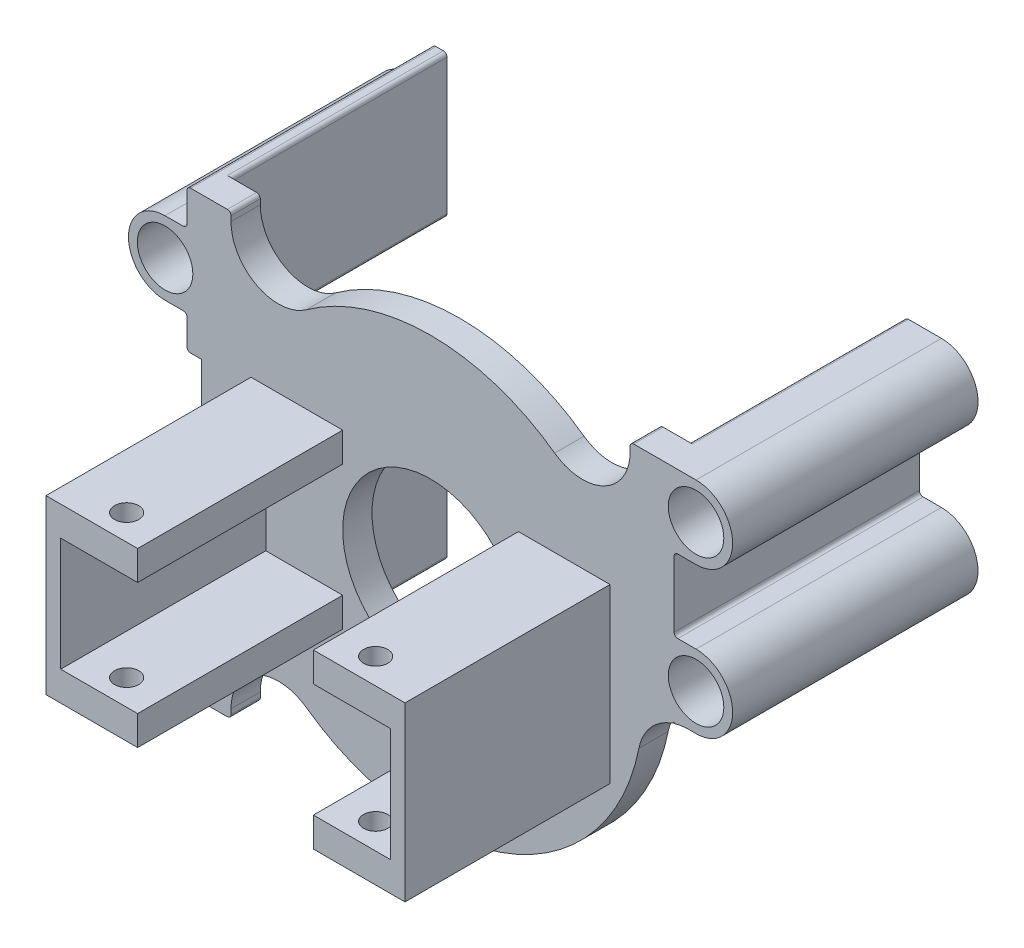
SolidWorks part; units mm, degrees
ref_plane "Front Plane" through (0, 0, 0) normal (0, 0, 1) x (1, 0, 0)
ref_plane "Top Plane" through (0, 0, 0) normal (0, 1, 0) x (1, 0, 0)
ref_plane "Right Plane" through (0, 0, 0) normal (1, 0, 0) x (0, 0, -1)
sketch "Sketch1" plane through (0, 0, 0) normal (0, 0, 1) x (1, 0, 0)
  line L15 (-5, 56.25) -> (-2.51, 56.25)
  line L22 (67.5, 41.2517) -> (65.01, 41.2517)
  line L27 (64.51, 50.75) -> (64.51, 41.7517)
  line L28 (66.555, 31.2587) -> (67.5, 31.2517)
  line L30 (-2.01, 60.75) -> (-2.01, 56.75)
  line L33 (-5, 46.25) -> (-2.51, 46.25)
  line L35 (-5, 16.25) -> (-2.51, 16.25)
  line L36 (-2.01, 5.75) -> (-2.01, 1.75)
  line L37 (-5, 6.25) -> (-2.51, 6.25)
  line L39 (-1.51, 1.25) -> (3.5, 1.25)
  line L40 (67.5, 51.25) -> (65.01, 51.25)
  line L43 (58.5, 60.75) -> (58.5, 60.0543)
  line L44 (67.5, 61.25) -> (59, 61.25)
  line L45 (3.5, 61.25) -> (-1.51, 61.25)
  line L46 (4, 2.4457) -> (4, 1.75)
  line L47 (4, 60.75) -> (4, 60.0543)
  line L48 (-2.01, 45.75) -> (-2.01, 42.25)
  line L49 (-2.01, 20.25) -> (-2.01, 16.75)
  line L52 (-1.51, 41.75) -> (0, 41.75)
  line L54 (-1.51, 20.75) -> (0, 20.75)
  line L55 (0, 41.75) -> (0, 20.75)
  circle A3 centre (-5, 51.25) radius 1.79
  circle A4 centre (-5, 11.25) radius 1.79
  arc A7 (-5, 56.25) -> (-5, 46.25) centre (-5, 51.25) ccw
  arc A8 (-5, 16.25) -> (-5, 6.25) centre (-5, 11.25) ccw
  arc A9 (67.5, 51.25) -> (67.5, 61.25) centre (67.5, 56.25) ccw
  arc A15 (66.555, 31.2587) -> (59.6979, 25.6181) centre (66.5646, 24.2587) ccw
  arc A23 (65.01, 51.25) -> (64.51, 50.75) centre (65.01, 50.75) ccw
  arc A27 (-2.51, 6.25) -> (-2.01, 5.75) centre (-2.51, 5.75) cw
  arc A28 (-2.51, 16.25) -> (-2.01, 16.75) centre (-2.51, 16.75) ccw
  arc A29 (-2.51, 46.25) -> (-2.01, 45.75) centre (-2.51, 45.75) cw
  arc A30 (-2.51, 56.25) -> (-2.01, 56.75) centre (-2.51, 56.75) ccw
  arc A34 (67.5, 31.2517) -> (67.5, 41.2517) centre (67.5, 36.2517) ccw
  arc A35 (65.01, 41.2517) -> (64.51, 41.7517) centre (65.01, 41.7517) cw
  circle A36 centre (67.5, 36.2517) radius 1.79
  circle A37 centre (31.25, 31.25) radius 12
  arc A41 (48.2007, 54.7803) -> (14.2993, 54.7803) centre (31.25, 31.25) ccw
  arc A42 (14.2993, 7.7197) -> (59.6979, 25.6181) centre (31.25, 31.25) ccw
  arc A43 (59, 61.25) -> (58.5, 60.75) centre (59, 60.75) ccw
  arc A44 (3.5, 1.25) -> (4, 1.75) centre (3.5, 1.75) ccw
  arc A45 (-2.01, 1.75) -> (-1.51, 1.25) centre (-1.51, 1.75) ccw
  arc A46 (3.5, 61.25) -> (4, 60.75) centre (3.5, 60.75) cw
  arc A47 (-1.51, 61.25) -> (-2.01, 60.75) centre (-1.51, 60.75) ccw
  arc A48 (14.2993, 7.7197) -> (4, 2.4457) centre (10.5, 2.4457) ccw
  arc A49 (48.2007, 54.7803) -> (58.5, 60.0543) centre (52, 60.0543) ccw
  arc A50 (14.2993, 54.7803) -> (4, 60.0543) centre (10.5, 60.0543) cw
  arc A51 (-2.01, 42.25) -> (-1.51, 41.75) centre (-1.51, 42.25) ccw
  arc A52 (-2.01, 20.25) -> (-1.51, 20.75) centre (-1.51, 20.25) cw
  circle A53 centre (67.5, 56.25) radius 1.79
extrude "Boss-Extrude1" add sketch "Sketch1" along normal blind 61.5
sketch "Sketch2" plane through (0, 0, 0) normal (0, 0, 1) x (1, 0, 0)
  line L2 (0, 1.75) -> (0, 20.25)
  line L4 (62.5, 1.25) -> (62.5, 29.9577)
  line L5 (66.555, 31.2587) -> (63, 31.2587)
  line L7 (62.5, 31.7587) -> (62.5, 60.75)
  line L9 (62.5, 61.25) -> (0, 61.25)
  line L14 (0, 1.25) -> (62.5, 1.25)
  line L17 (0, 61.25) -> (-0.5, 61.25)
  line L54 (0, 41.75) -> (-0.5, 41.75)
  line L55 (63, 61.25) -> (62.5, 61.25)
  line L56 (0, 42.25) -> (0, 60.75)
  line L57 (0, 20.75) -> (-0.5, 20.75)
  line L58 (0, 20.75) -> (0, 41.75)
  line L61 (0, 1.25) -> (-0.5, 1.25)
  arc A0 (0, 60.75) -> (-0.5, 61.25) centre (-0.5, 60.75) ccw
  arc A10 (63, 31.2587) -> (62.5, 31.7587) centre (63, 31.7587) cw
  arc A11 (66.555, 31.2587) -> (62.5, 29.9577) centre (66.5646, 24.2587) ccw
  arc A13 (63, 61.25) -> (62.5, 60.75) centre (63, 60.75) ccw
  arc A14 (-0.5, 1.25) -> (0, 1.75) centre (-0.5, 1.75) ccw
  arc A16 (0, 20.25) -> (-0.5, 20.75) centre (-0.5, 20.25) ccw
  arc A17 (-0.5, 41.75) -> (0, 42.25) centre (-0.5, 42.25) ccw
extrude "Cut-Extrude1" cut sketch "Sketch2" along normal blind 29.5
sketch "Sketch3" plane through (0, 0, 61.5) normal (0, 0, 1) x (1, 0, 0)
  line L14 (64.51, 31.3102) -> (64.51, 30.9504)
  arc A2 (64.51, 31.3102) -> (64.1803, 30.8401) centre (64.01, 31.3102) cw
  arc A9 (64.51, 30.9504) -> (64.1803, 30.8401) centre (66.5646, 24.2587) ccw
  circle A10 centre (67.5, 36.2517) radius 3.79
  circle A11 centre (-5, 11.25) radius 3.79
  circle A12 centre (-5, 51.25) radius 3.79
  circle A13 centre (67.5, 56.25) radius 3.79
extrude "Cut-Extrude2" cut sketch "Sketch3" against normal offset from surface (54.5 mm away) 7 up to face at (69.29, 56.25, 0)
sketch "Sketch4" plane through (0, 0, 61.5) normal (0, 0, 1) x (1, 0, 0)
  line L1 (19.25, 43.02) -> (6.74, 43.02)
  line L2 (8.75, 23.5) -> (19.25, 23.5)
  line L4 (8.75, 39) -> (19.25, 39)
  line L5 (19.25, 19.48) -> (6.74, 19.48)
  line L6 (43.25, 19.48) -> (55.76, 19.48)
  line L11 (43.25, 19.48) -> (43.25, 23.5)
  line L13 (43.25, 39) -> (43.25, 43.02)
  line L14 (8.75, 23.5) -> (8.75, 39)
  line L15 (19.25, 39) -> (19.25, 43.02)
  line L16 (19.25, 19.48) -> (19.25, 23.5)
  line L24 (43.25, 23.5) -> (53.75, 23.5)
  line L26 (43.25, 39) -> (53.75, 39)
  line L27 (6.74, 19.48) -> (6.74, 43.02)
  line L30 (55.76, 19.48) -> (55.76, 43.02)
  line L32 (53.75, 23.5) -> (53.75, 39)
  line L35 (55.76, 43.02) -> (43.25, 43.02)
extrude "Cut-Extrude3" cut sketch "Sketch4" against normal offset from surface (28 mm away) 4 flip side to cut up to face at (43.25, 31.25, 29.5)
sketch "Sketch5" plane through (0, 43.02, 0) normal (0, 1, 0) x (1, 0, 0)
  circle A2 centre (48.25, -58) radius 1.65
  circle A3 centre (14.25, -58) radius 1.65
extrude "Cut-Extrude4" cut sketch "Sketch5" against normal up to surface (23.54 mm away) up to face at (12.995, 19.48, 47.5)
